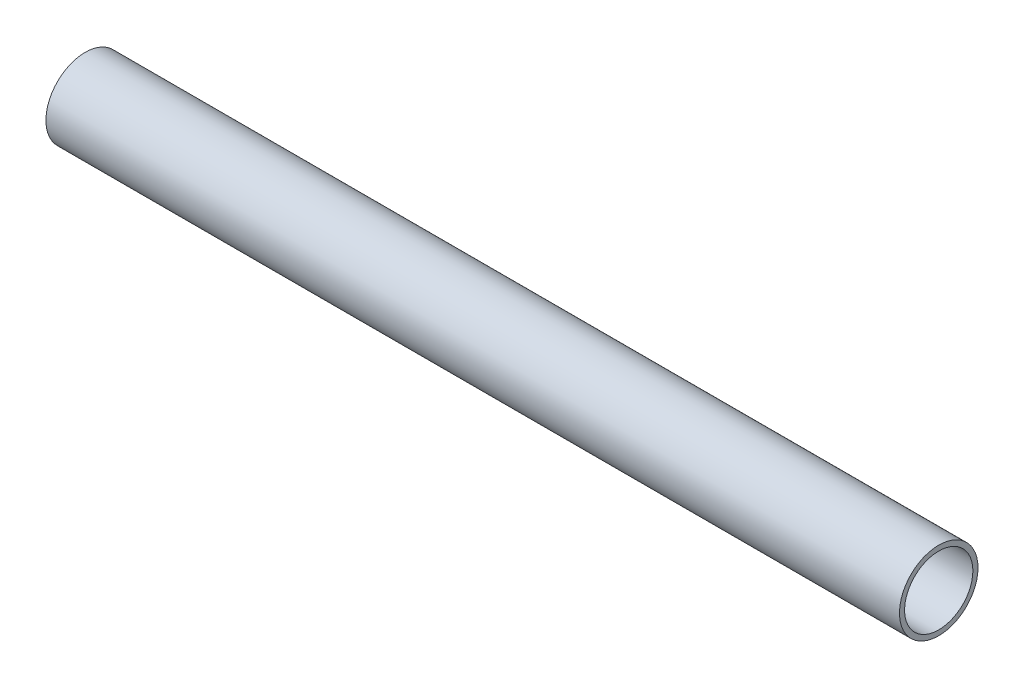
SolidWorks part; units mm, degrees
ref_plane "Front Plane" through (0, 0, 0) normal (0, 0, 1) x (1, 0, 0)
ref_plane "Top Plane" through (0, 0, 0) normal (0, 1, 0) x (1, 0, 0)
ref_plane "Right Plane" through (0, 0, 0) normal (1, 0, 0) x (0, 0, -1)
sketch "Sketch1" plane through (0, 0, 0) normal (1, 0, 0) x (0, 0, -1)
  circle A0 centre (0, 0) radius 11.5
  dimension "D1" = 23
extrude "Extrude-Thin1" add sketch "Sketch1" along normal blind 250 thin thin type one direction reverse wall 1.5
